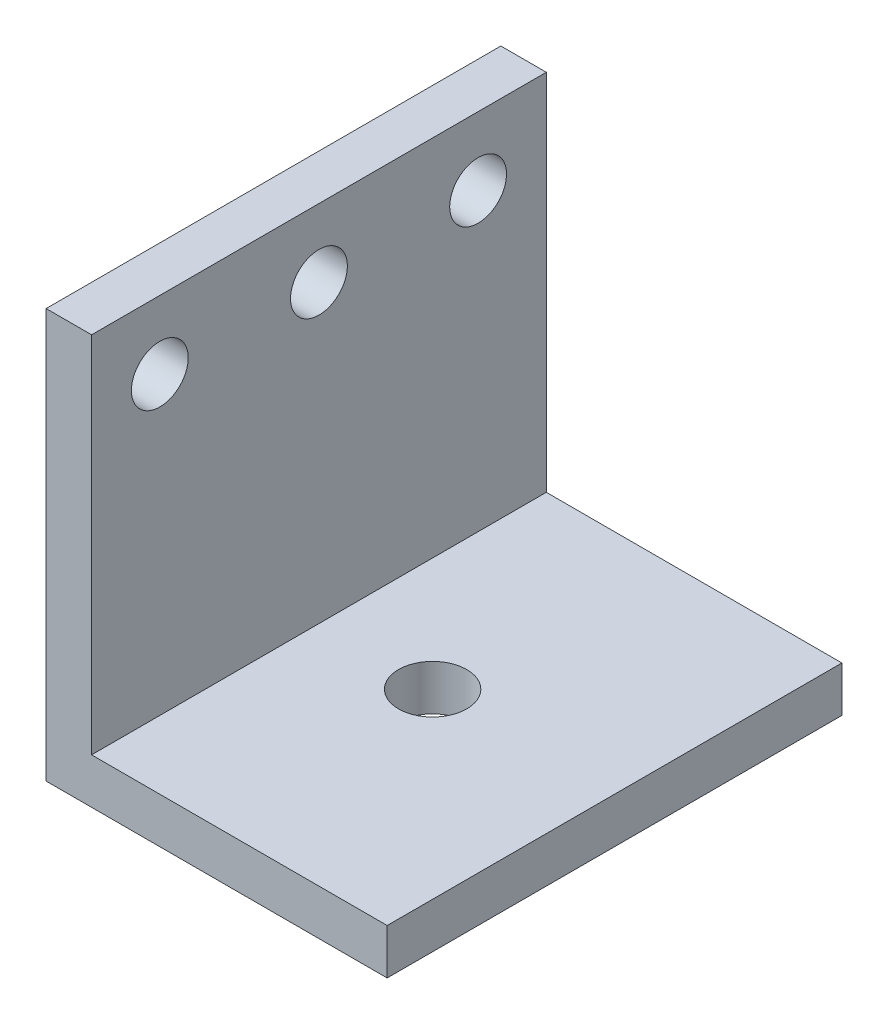
SolidWorks part; units mm, degrees
ref_plane "Alzado" through (0, 0, 0) normal (0, 0, 1) x (1, 0, 0)
ref_plane "Planta" through (0, 0, 0) normal (0, 1, 0) x (1, 0, 0)
ref_plane "Vista lateral" through (0, 0, 0) normal (1, 0, 0) x (0, 0, -1)
sketch "Croquis1" plane through (0, 0, 0) normal (0, 0, 1) x (1, 0, 0)
  line L0 (0, 90) -> (0, 0)
  line L1 (0, 0) -> (75, 0)
  dimension "D1" = 90
  dimension "D2" = 75
extrude "Extruir-Lámina1" add sketch "Croquis1" along normal blind 100 thin thin type one direction reverse wall 10
sketch "Croquis2" plane through (0, 0, 0) normal (-1, 0, 0) x (0, 0, 1)
  line L0 (0, 75) -> (100, 75) construction
  line L1 (0, 90) -> (0, 0) construction
  line L2 (100, 90) -> (100, 0) construction
  line L3 (100, 90) -> (0, 90) construction
  circle A0 centre (15, 75) radius 6.25
  circle A1 centre (50, 75) radius 6.25
  circle A2 centre (85, 75) radius 6.25
  point P14 (0, 0)
  point P15 (50, 90)
  dimension "D2" = 12.5
  dimension "D3" = 35
  dimension "D4" = 35
  dimension "D1" = 15
extrude "Cortar-Extruir1" cut sketch "Croquis2" against normal blind 10
sketch "Croquis3" plane through (0, 10, 0) normal (0, 1, 0) x (1, 0, 0)
  line L0 (75, -100) -> (75, 0) construction
  circle A0 centre (35, -50) radius 7.5
  point P4 (0, 0)
  point P5 (75, -50)
  dimension "D1" = 40
  dimension "D2" = 15
extrude "Cortar-Extruir2" cut sketch "Croquis3" against normal blind 10
